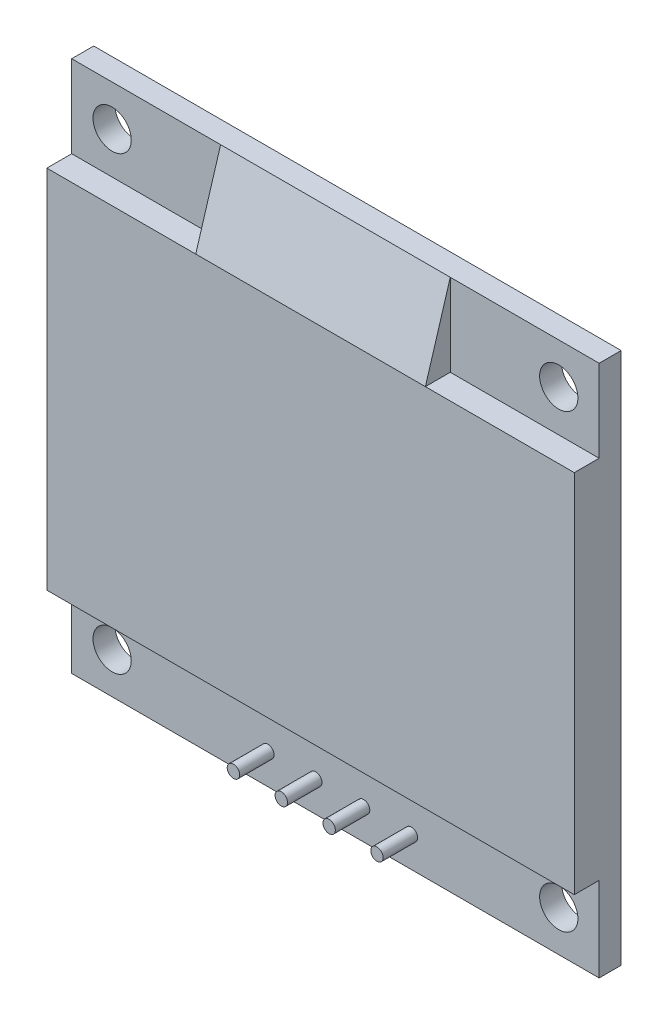
SolidWorks part; units mm, degrees
ref_plane "Plan de face" through (0, 0, 0) normal (0, 0, 1) x (1, 0, 0)
ref_plane "Plan de dessus" through (0, 0, 0) normal (0, 1, 0) x (1, 0, 0)
ref_plane "Plan de droite" through (0, 0, 0) normal (1, 0, 0) x (0, 0, -1)
sketch "Esquisse1" plane through (0, 0, 0) normal (0, 0, 1) x (1, 0, 0)
  line L1 (-13.78, 13.91) -> (13.78, 13.91)
  line L2 (-13.78, 13.91) -> (-13.78, -13.91)
  line L3 (-13.78, -13.91) -> (13.78, -13.91)
  line L4 (13.78, 13.91) -> (13.78, -13.91)
  line L5 (-13.78, 13.91) -> (13.78, -13.91) construction
  line L6 (-13.78, -13.91) -> (13.78, 13.91) construction
  circle A0 centre (-11.6687, 11.7787) radius 1
  circle A1 centre (11.6687, 11.7787) radius 1
  circle A2 centre (-11.6687, -11.7787) radius 1
  circle A3 centre (11.6687, -11.7787) radius 1
  point P0 (0, 0)
  dimension "D3" = 2
  dimension "D1" = 27.56
  dimension "D2" = 27.82
  dimension "D4" = 3
  dimension "D5" = 3
  dimension "D6" = 3
  dimension "D7" = 3
extrude "Boss.-Extru.1" add sketch "Esquisse1" along normal blind 1.15
sketch "Esquisse3" plane through (0, 0, 1.15) normal (0, 0, 1) x (1, 0, 0)
  line L0 (-13.78, 13.91) -> (-13.78, -13.91) construction
  line L1 (-13.78, 9.61) -> (13.78, 9.61)
  line L2 (-13.78, 9.61) -> (-13.78, -9.49)
  line L3 (-13.78, -9.49) -> (13.78, -9.49)
  line L4 (13.78, 9.61) -> (13.78, -9.49)
  line L5 (13.78, -13.91) -> (13.78, 13.91) construction
  line L6 (13.78, 13.91) -> (-13.78, 13.91) construction
  dimension "D1" = 4.3
  dimension "D2" = 19.1
extrude "Boss.-Extru.2" add sketch "Esquisse3" along normal blind 1.3
sketch "Esquisse4" plane through (0, 0, 1.15) normal (0, 0, 1) x (1, 0, 0)
  line L0 (-7.1868, -12.31) -> (8.2951, -12.31) construction
  line L1 (-13.78, -13.91) -> (13.78, -13.91) construction
  line L2 (-13.78, -9.49) -> (-13.78, -13.91) construction
  circle A0 centre (-3.53, -12.31) radius 0.325
  dimension "D2" = 0.65
  dimension "D1" = 1.6
  dimension "D3" = 10.25
extrude "Boss.-Extru.3" add sketch "Esquisse4" along normal blind 1.8 and the other way blind 10.1
pattern_linear "Répétition linéaire1" count 4 spacing 2.5 along (1, 0, 0) of "Boss.-Extru.3"
sketch "Esquisse5" plane through (0, 0, 0) normal (0, 0, -1) x (-1, 0, 0)
  line L1 (1.0483, -6.3083) -> (7.566, -6.3083)
  line L2 (1.0483, -6.3083) -> (1.0483, -8.0093)
  line L3 (1.0483, -8.0093) -> (7.566, -8.0093)
  line L4 (7.566, -6.3083) -> (7.566, -8.0093)
  dimension "D1" = 6.5177
extrude "Boss.-Extru.4" add sketch "Esquisse5" along normal blind 0.5
sketch "Esquisse6" plane through (0, 0, 0) normal (0, 0, -1) x (-1, 0, 0)
  line L0 (-3.97, -12.31) -> (3.53, -12.31) construction
  line L1 (-5.22, -11.06) -> (4.78, -11.06)
  line L2 (-5.22, -11.06) -> (-5.22, -13.56)
  line L3 (-5.22, -13.56) -> (4.78, -13.56)
  line L4 (4.78, -11.06) -> (4.78, -13.56)
  dimension "D1" = 2.5
  dimension "D2" = 1.25
  dimension "D3" = 1.25
extrude "Boss.-Extru.5" add sketch "Esquisse6" along normal blind 2.3
sketch "Esquisse7" plane through (0, 0, 0) normal (1, 0, 0) x (0, 0, -1)
  line L0 (-1.15, 13.91) -> (-2.45, 9.61)
  line L1 (-1.15, 13.91) -> (-1.15, 9.61) construction
  line L2 (-2.45, 9.61) -> (-1.15, 9.61) construction
  line L3 (-1.15, 13.91) -> (-1.15, 9.61)
  line L4 (-2.45, 9.61) -> (-1.15, 9.61)
extrude "Boss.-Extru.6" add sketch "Esquisse7" along normal mid plane 12
